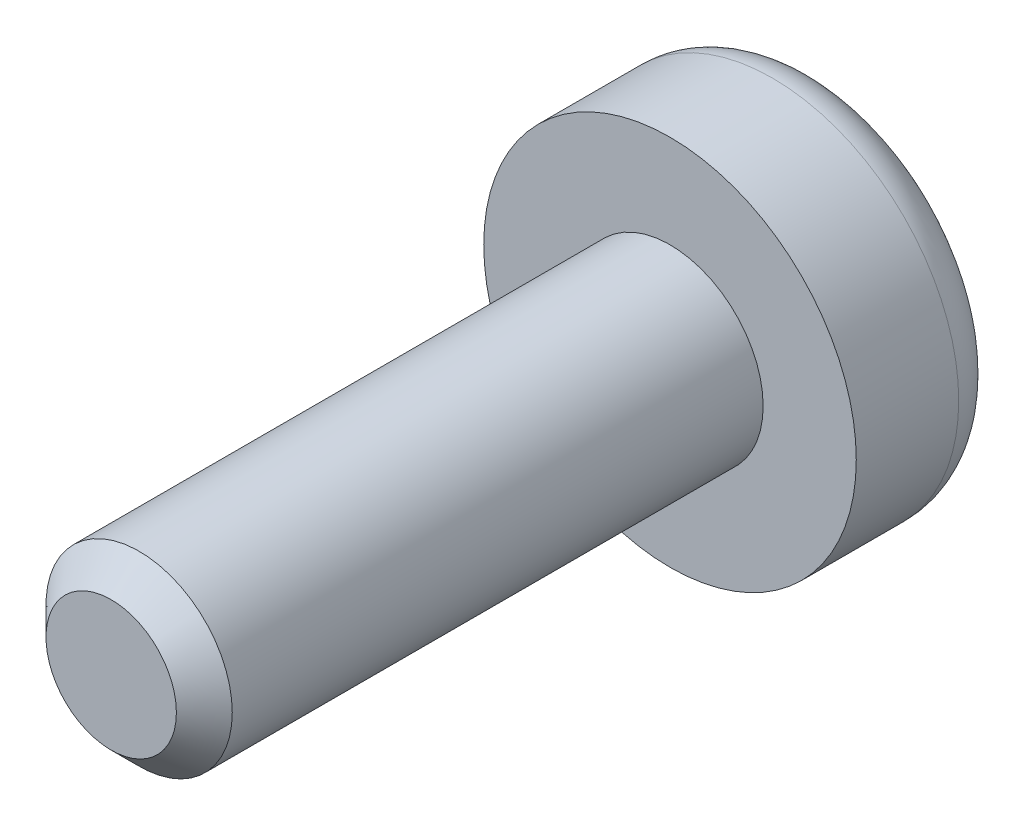
SolidWorks part; units mm, degrees
ref_plane "Front Plane" through (0, 0, 0) normal (0, 0, 1) x (1, 0, 0)
ref_plane "Top Plane" through (0, 0, 0) normal (0, 1, 0) x (1, 0, 0)
ref_plane "Right Plane" through (0, 0, 0) normal (1, 0, 0) x (0, 0, -1)
sketch "Sketch1" plane through (0, 0, 0) normal (0, 0, 1) x (1, 0, 0)
  circle A0 centre (0, 0) radius 2
  dimension "D1" = 4
extrude "Extrude1" add sketch "Sketch1" along normal blind 1.6
sketch "Sketch2" plane through (0, 0, 1.6) normal (0, 0, 1) x (1, 0, 0)
  circle A0 centre (0, 0) radius 1
extrude "Extrude2" add sketch "Sketch2" along normal blind 6
sketch "Sketch3" plane through (0, 0, 0) normal (0, 0, -1) x (-1, 0, 0)
  line L0 (0.3034, -0.2801) -> (0.3034, -1.2585)
  line L1 (-0.3315, 1.3894) -> (0.3034, 1.3894)
  line L2 (-0.3315, 1.3894) -> (-0.3315, 0.3828)
  line L3 (-0.3315, -1.2585) -> (0.3034, -1.2585)
  line L4 (0.3034, 1.3894) -> (0.3034, 0.3828)
  line L5 (-1.3439, 0.3828) -> (-0.3315, 0.3828)
  line L6 (-1.3439, 0.3828) -> (-1.3439, -0.2801)
  line L7 (-1.3439, -0.2801) -> (-0.3315, -0.2801)
  line L8 (1.2853, 0.3828) -> (1.2853, -0.2801)
  line L9 (-0.3315, -0.2801) -> (-0.3315, -1.2585)
  line L10 (0.3034, -0.2801) -> (1.2853, -0.2801)
  line L11 (0.3034, 0.3828) -> (1.2853, 0.3828)
extrude "Cut-Extrude1" cut sketch "Sketch3" against normal blind 0.5
fillet "Fillet1" radius 0.2 4 edges at (0.3315, -0.2801, 0.25) (-0.3034, -0.2801, 0.25) (-0.3034, 0.3828, 0.25) (0.3315, 0.3828, 0.25)
chamfer "Chamfer1" distance 0.3 angle 45 1 edges at (1, 0, 7.6)
fillet "Fillet2" radius 0.5 1 edges at (2, 0, 0)
